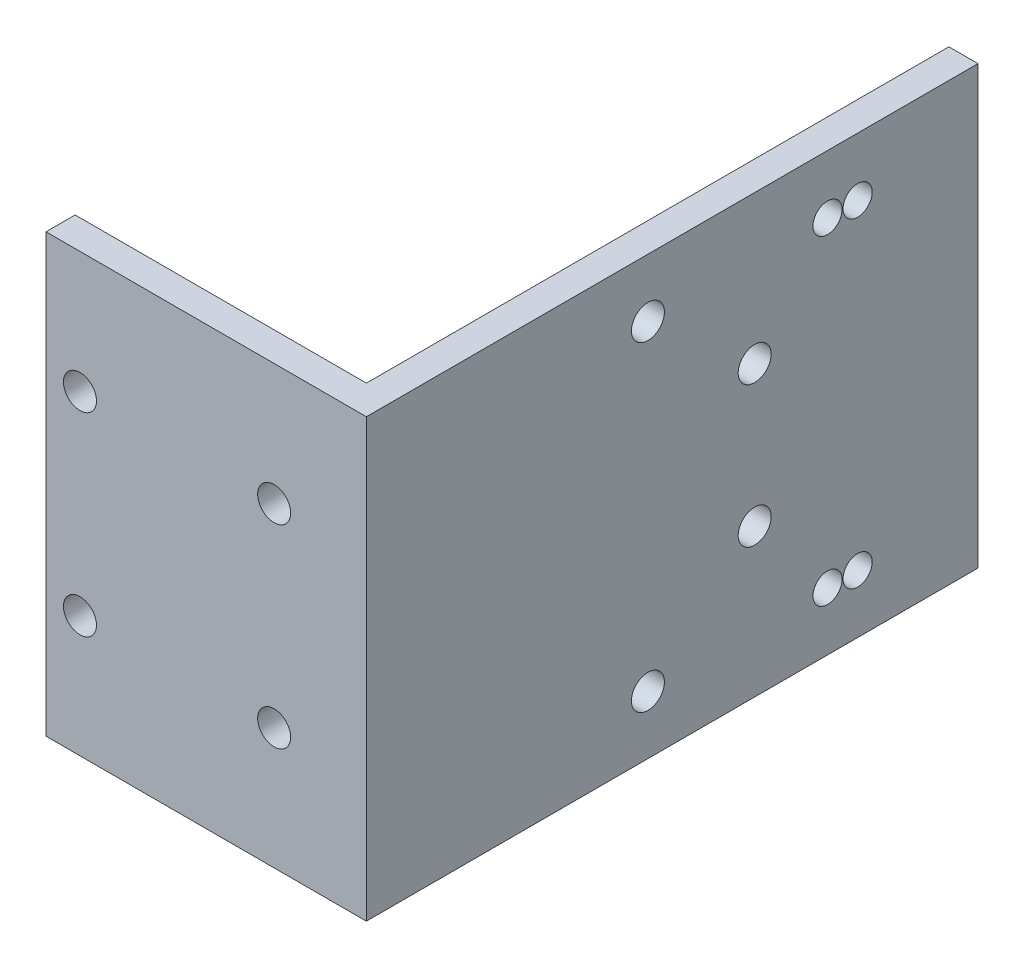
SolidWorks part; units mm, degrees
ref_plane "前视基准面" through (0, 0, 0) normal (0, 0, 1) x (1, 0, 0)
ref_plane "上视基准面" through (0, 0, 0) normal (0, 1, 0) x (1, 0, 0)
ref_plane "右视基准面" through (0, 0, 0) normal (1, 0, 0) x (0, 0, -1)
sketch "草图1" plane through (0, 0, 0) normal (0, 1, 0) x (1, 0, 0)
  line L0 (0, 0) -> (30, 0)
  line L1 (30, 0) -> (30, 60)
  line L2 (0, -3) -> (33, -3)
  line L3 (33, -3) -> (33, 60)
  line L4 (30, 60) -> (33, 60)
  line L5 (0, 0) -> (0, -3)
  dimension "D1" = 30
  dimension "D2" = 60
  dimension "D3" = 3
extrude "凸台-拉伸1" add sketch "草图1" along normal blind 45
sketch "草图2" plane through (0, 0, 3) normal (0, 0, 1) x (1, 0, 0)
  line L0 (0, 45) -> (33, 45) construction
  line L2 (0, 45) -> (0, 0) construction
  circle A0 centre (3.5, 32.5) radius 1.7
  circle A1 centre (23.5, 32.5) radius 1.7
  circle A2 centre (23.5, 12.5) radius 1.7
  circle A3 centre (3.5, 12.5) radius 1.7
  dimension "D5" = 3.4
  dimension "D1" = 20
  dimension "D2" = 20
  dimension "D3" = 12.5
  dimension "D4" = 3.5
extrude "切除-拉伸1" cut sketch "草图2" against normal up to next
sketch "草图3" plane through (33, 0, 0) normal (1, 0, 0) x (0, 0, -1)
  line L0 (-3, 0) -> (60, 0) construction
  line L1 (60, 45) -> (60, 0) construction
  line L2 (-3, 45) -> (-3, 0) construction
  line L3 (-3, 45) -> (60, 45) construction
  line L4 (-18.4473, 22.5) -> (76.5611, 22.5) construction
  circle A0 centre (26, 6) radius 1.7
  circle A1 centre (26, 39) radius 1.7
  circle A2 centre (37, 15.25) radius 1.7
  circle A3 centre (37, 29.75) radius 1.7
  circle A4 centre (44.5, 39) radius 1.5
  circle A5 centre (47.6, 6) radius 1.5
  circle A6 centre (47.6, 39) radius 1.5
  circle A7 centre (44.5, 6) radius 1.5
  dimension "D4" = 3.4
  dimension "D5" = 33
  dimension "D9" = 3
  dimension "D10" = 6
  dimension "D12" = 22.5
  dimension "D1" = 14.5
  dimension "D2" = 15.25
  dimension "D3" = 23
  dimension "D6" = 6
  dimension "D7" = 11
  dimension "D8" = 47.5
  dimension "D11" = 3.1
extrude "切除-拉伸2" cut sketch "草图3" against normal up to next
